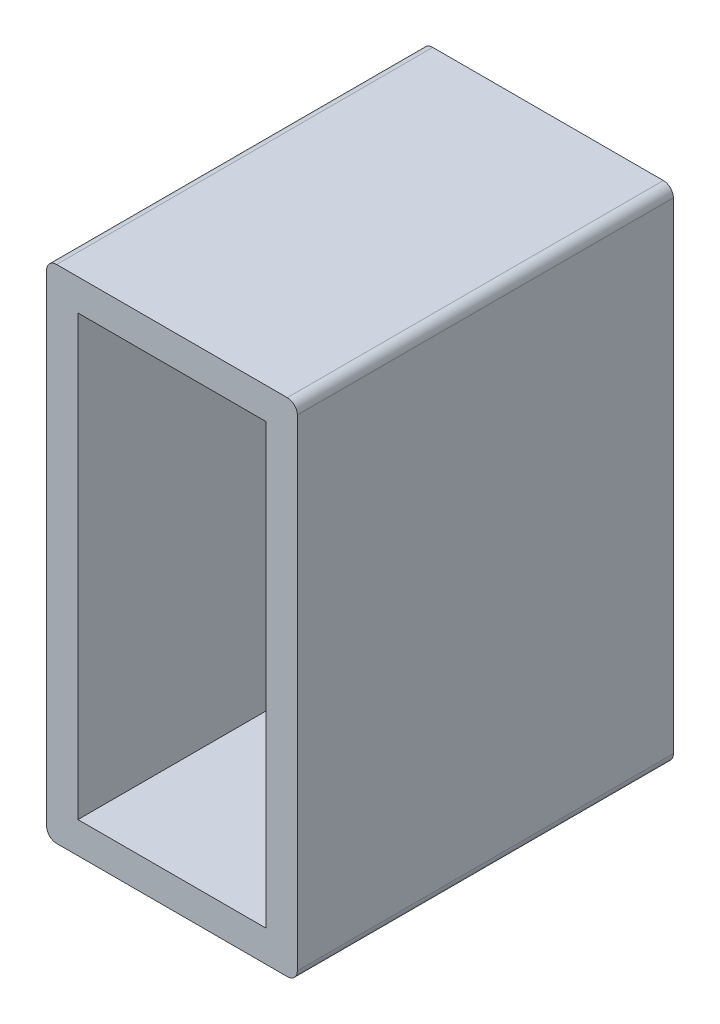
SolidWorks part; units mm, degrees
ref_plane "Front Plane" through (0, 0, 0) normal (0, 0, 1) x (1, 0, 0)
ref_plane "Top Plane" through (0, 0, 0) normal (0, 1, 0) x (1, 0, 0)
ref_plane "Right Plane" through (0, 0, 0) normal (1, 0, 0) x (0, 0, -1)
sketch "Sketch1" plane through (0, 0, 0) normal (0, 0, 1) x (1, 0, 0)
  line L0 (-9.525, 22.225) -> (9.525, 22.225)
  line L1 (-11.684, -25.4) -> (11.684, -25.4)
  line L2 (-12.7, -24.384) -> (-12.7, 24.384)
  line L3 (-11.684, 25.4) -> (11.684, 25.4)
  line L4 (12.7, -24.384) -> (12.7, 24.384)
  line L5 (-12.7, -25.4) -> (12.7, 25.4) construction
  line L6 (-12.7, 25.4) -> (12.7, -25.4) construction
  line L7 (9.525, -22.225) -> (9.525, 22.225)
  line L8 (-9.525, -22.225) -> (9.525, -22.225)
  line L9 (-9.525, -22.225) -> (-9.525, 22.225)
  arc A0 (-12.7, -24.384) -> (-11.684, -25.4) centre (-11.684, -24.384) ccw
  arc A1 (11.684, -25.4) -> (12.7, -24.384) centre (11.684, -24.384) ccw
  arc A2 (12.7, 24.384) -> (11.684, 25.4) centre (11.684, 24.384) ccw
  arc A3 (-11.684, 25.4) -> (-12.7, 24.384) centre (-11.684, 24.384) ccw
  arc A4 (9.525, 22.225) -> (9.525, 22.225) centre (9.525, 22.225) ccw
  arc A5 (9.525, -22.225) -> (9.525, -22.225) centre (9.525, -22.225) ccw
  arc A6 (-9.525, -22.225) -> (-9.525, -22.225) centre (-9.525, -22.225) ccw
  arc A7 (-9.525, 22.225) -> (-9.525, 22.225) centre (-9.525, 22.225) ccw
  point P0 (0, 0)
  dimension "D3" = 1.016
  dimension "D1" = 25.4
  dimension "D2" = 50.8
  dimension "D4" = 3.175
extrude "Boss-Extrude1" add sketch "Sketch1" along normal mid plane 38.1
